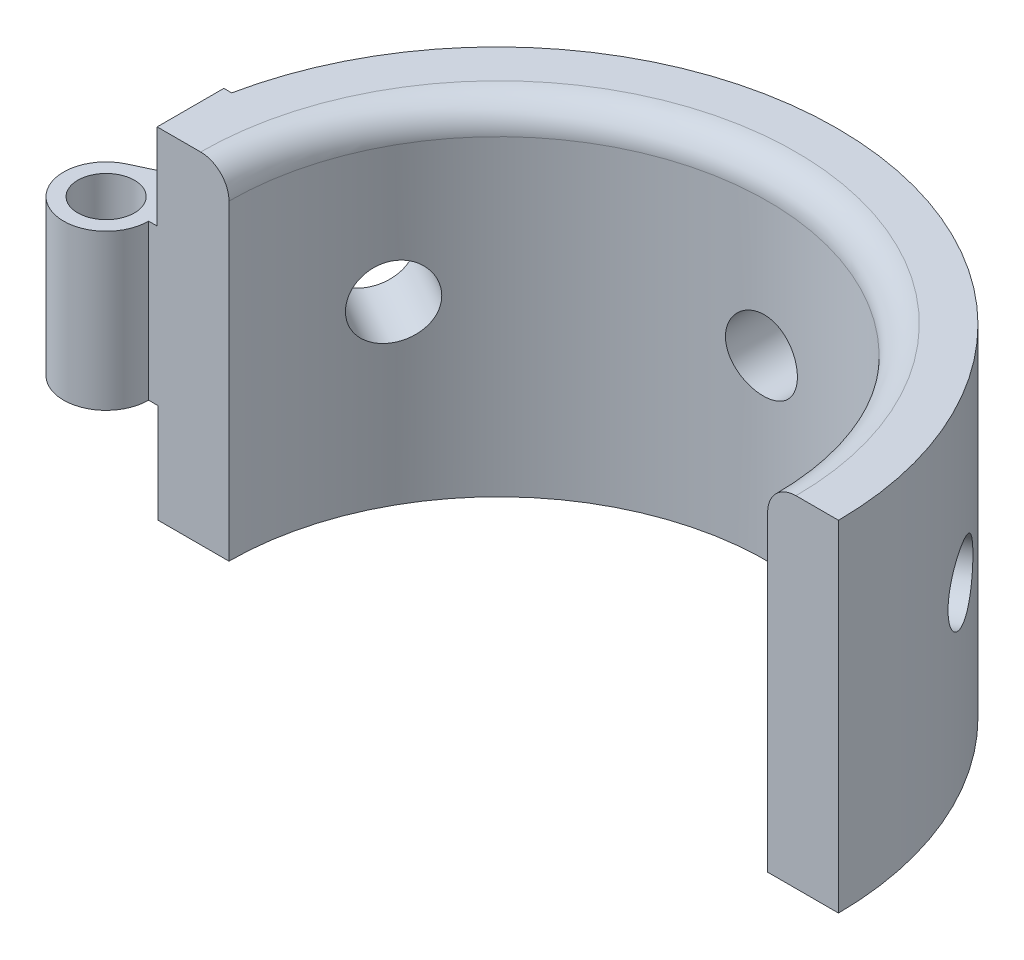
SolidWorks part; units mm, degrees
ref_plane "Front Plane" through (0, 0, 0) normal (0, 0, 1) x (1, 0, 0)
ref_plane "Top Plane" through (0, 0, 0) normal (0, 1, 0) x (1, 0, 0)
ref_plane "Right Plane" through (0, 0, 0) normal (1, 0, 0) x (0, 0, -1)
sketch "Sketch1" plane through (0, 0, 0) normal (0, 1, 0) x (1, 0, 0)
  line L1 (-78.9587, 0) -> (-17.9987, 0)
  arc A0 (-78.9587, 0) -> (-17.9987, 0) centre (-48.4787, -0.1303) cw
  dimension "D1" = 60.96
extrude "Boss-Extrude1" add sketch "Sketch1" along normal blind 30.48 contours L1 A0
ref_plane "Plane1" through (-17.9987, 30.48, 0) normal (1, 0, 0) x (0, 0, -1)
sketch "Sketch3" plane through (0, 0, 0) normal (0, 1, 0) x (1, 0, 0)
  line L0 (-78.9587, 0) -> (-17.9987, 0) construction
  circle A0 centre (-48.4787, 0) radius 24.13
  dimension "D1" = 48.26
extrude "Cut-Extrude4" cut sketch "Sketch3" along normal through all contours A0
sketch "Sketch4" plane through (0, 0, 0) normal (0, 0, 1) x (1, 0, 0)
  circle A0 centre (-48.8244, 15.7989) radius 3.175
  dimension "D1" = 6.35
extrude "Cut-Extrude5" cut sketch "Sketch4" against normal blind 63.754 contours A0
pattern_circular "CirPattern3" count 6 over 360 about axis through (-48.4787, 30.48, 0.1303) along (0, -1, 0) of "Cut-Extrude5"
sketch "Sketch8" plane through (0, 30.48, 0) normal (0, 1, 0) x (1, 0, 0)
  line L0 (-79.8054, 0) -> (-83.6154, 0)
  line L1 (-78.9587, 0) -> (-79.8054, 0)
  line L3 (-78.9587, 5.9753) -> (-79.8054, 5.9753)
  line L5 (-79.8054, 5.9753) -> (-85.2229, 3.4543)
  line L6 (-78.9587, 5.9753) -> (-78.3412, 5.9753)
  line L7 (-78.3412, 5.9753) -> (-78.3157, 5.9753)
  arc A0 (-85.2229, 3.4543) -> (-79.8054, 0) centre (-83.6154, 0) ccw
  circle A1 centre (-83.6154, 0) radius 2.54
  arc A2 (-17.9987, 0) -> (-78.9587, 0) centre (-48.4787, -0.1303) ccw construction
  dimension "D1" = 7.62
  dimension "D2" = 5.08
extrude "Boss-Extrude3" add sketch "Sketch8" against normal blind 21.59
sketch "Sketch9" plane through (0, 0, 0) normal (0, 0, 1) x (1, 0, 0)
  line L0 (-87.4254, 30.48) -> (-87.4254, 8.89) construction
  line L1 (-79.8054, 30.48) -> (-87.4254, 30.48)
  line L2 (-79.8054, 30.48) -> (-79.8054, 22.786)
  line L3 (-79.8054, 22.786) -> (-87.4254, 22.786)
  line L4 (-87.4254, 30.48) -> (-87.4254, 22.786)
extrude "Cut-Extrude7" cut sketch "Sketch9" against normal through all both and the other way through all
sketch "Sketch10" plane through (0, 0, 0) normal (0, 0, 1) x (1, 0, 0)
  line L1 (-79.8054, 30.48) -> (-79.0434, 30.48)
  line L2 (-79.8054, 30.48) -> (-79.8054, 22.786)
  line L3 (-79.8054, 22.786) -> (-79.0434, 22.786)
  line L4 (-79.0434, 30.48) -> (-79.0434, 22.786)
  dimension "D1" = 0.762
extrude "Cut-Extrude8" cut sketch "Sketch10" against normal blind 21.59
fillet "Fillet1" radius 2.54 1 edges at (-48.4787, 30.48, -24.13)
